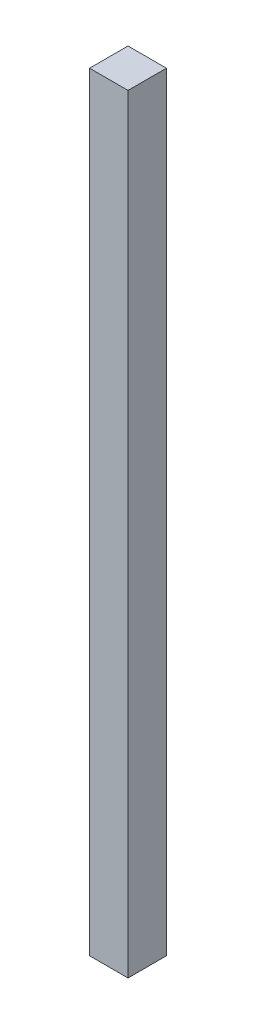
SolidWorks part; units mm, degrees
ref_plane "Ebene vorne" through (0, 0, 0) normal (0, 0, 1) x (1, 0, 0)
ref_plane "Ebene oben" through (0, 0, 0) normal (0, 1, 0) x (1, 0, 0)
ref_plane "Ebene rechts" through (0, 0, 0) normal (1, 0, 0) x (0, 0, -1)
sketch "Skizze2" plane through (0, 0, 0) normal (0, 1, 0) x (1, 0, 0)
  line L1 (-10, -10) -> (10, -10)
  line L2 (-10, -10) -> (-10, 10)
  line L3 (-10, 10) -> (10, 10)
  line L4 (10, -10) -> (10, 10)
  line L5 (-10, -10) -> (10, 10) construction
  line L6 (-10, 10) -> (10, -10) construction
  point P0 (0, 0)
  dimension "D1" = 20
  dimension "D2" = 20
extrude "Aufsatz-Linear austragen1" add sketch "Skizze2" along normal blind 400
